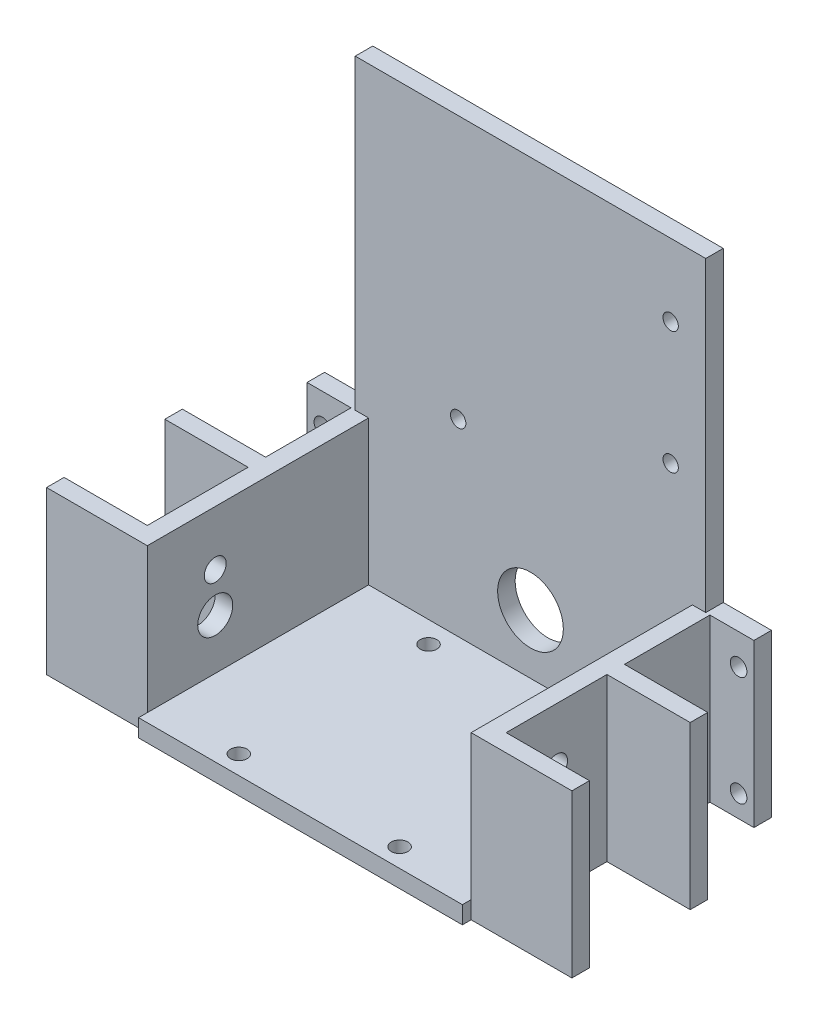
SolidWorks part; units mm, degrees
ref_plane "Front Plane" through (0, 0, 0) normal (0, 0, 1) x (1, 0, 0)
ref_plane "Top Plane" through (0, 0, 0) normal (0, 1, 0) x (1, 0, 0)
ref_plane "Right Plane" through (0, 0, 0) normal (1, 0, 0) x (0, 0, -1)
sketch "Sketch1" plane through (0, 0, 0) normal (0, 1, 0) x (1, 0, 0)
  line L0 (40.9555, 11.5) -> (59.9555, 11.5)
  line L1 (-59.9555, -15.5) -> (59.9555, -15.5)
  line L2 (-59.9555, -15.5) -> (-59.9555, -11.5)
  line L3 (-59.9555, 15.5) -> (59.9555, 15.5)
  line L4 (59.9555, -15.5) -> (59.9555, -11.5)
  line L5 (-59.9555, -15.5) -> (59.9555, 15.5) construction
  line L6 (-59.9555, 15.5) -> (59.9555, -15.5) construction
  line L8 (-40.9555, -11.5) -> (-40.9555, 11.5)
  line L10 (40.9555, -11.5) -> (40.9555, 11.5)
  line L11 (-40.9555, -11.5) -> (40.9555, 11.5) construction
  line L12 (-40.9555, 11.5) -> (40.9555, -11.5) construction
  line L14 (59.9555, -11.5) -> (40.9555, -11.5)
  line L15 (-40.9555, -11.5) -> (-59.9555, -11.5)
  line L16 (59.9555, 11.5) -> (59.9555, 15.5)
  line L17 (-59.9555, 11.5) -> (-40.9555, 11.5)
  line L18 (-59.9555, 11.5) -> (-59.9555, 15.5)
  point P0 (0, 0)
  point P6 (0, 0)
  dimension "D1" = 23
  dimension "D2" = 19
  dimension "D3" = 4
extrude "Boss-Extrude1" add sketch "Sketch1" along normal blind 4
sketch "Sketch2" plane through (0, 4, 0) normal (0, 1, 0) x (1, 0, 0)
  line L12 (-36.9555, 15.5) -> (-59.9555, 15.5)
  line L14 (-36.9555, -15.5) -> (-36.9555, 15.5)
  line L16 (36.9555, -15.5) -> (36.9555, 15.5)
  line L17 (-36.9555, -15.5) -> (36.9555, 15.5) construction
  line L18 (-36.9555, 15.5) -> (36.9555, -15.5) construction
  line L19 (36.9555, -15.5) -> (59.9555, -15.5)
  line L24 (59.9555, 11.5) -> (59.9555, 15.5)
  line L25 (59.9555, 15.5) -> (-59.9555, 15.5)
  line L26 (-59.9555, 15.5) -> (-59.9555, 11.5)
  line L27 (-59.9555, 11.5) -> (-40.9555, 11.5)
  line L28 (-40.9555, 11.5) -> (-40.9555, -11.5)
  line L29 (-40.9555, -11.5) -> (-59.9555, -11.5)
  line L30 (-59.9555, -11.5) -> (-59.9555, -15.5)
  line L31 (-59.9555, -15.5) -> (59.9555, -15.5)
  line L32 (59.9555, -15.5) -> (59.9555, -11.5)
  line L33 (59.9555, -11.5) -> (40.9555, -11.5)
  line L34 (40.9555, -11.5) -> (40.9555, 11.5)
  line L35 (40.9555, 11.5) -> (59.9555, 11.5)
  line L36 (59.9555, 11.5) -> (59.9555, 15.5)
  line L37 (59.9555, 15.5) -> (36.9555, 15.5)
  line L38 (-59.9555, 15.5) -> (-59.9555, 11.5)
  line L39 (-59.9555, 11.5) -> (-40.9555, 11.5)
  line L40 (-40.9555, 11.5) -> (-40.9555, -11.5)
  line L41 (-40.9555, -11.5) -> (-59.9555, -11.5)
  line L42 (-59.9555, -11.5) -> (-59.9555, -15.5)
  line L43 (-59.9555, -15.5) -> (-36.9555, -15.5)
  line L44 (59.9555, -15.5) -> (59.9555, -11.5)
  line L45 (59.9555, -11.5) -> (40.9555, -11.5)
  line L46 (40.9555, -11.5) -> (40.9555, 11.5)
  line L47 (40.9555, 11.5) -> (59.9555, 11.5)
  point P2 (0, 0)
  dimension "D2" = 4
  dimension "D1" = 0
extrude "Boss-Extrude2" add sketch "Sketch2" along normal blind 37 from surface at -4 starting at face at (0, 0, 0)
sketch "Sketch3" plane through (-40.9555, 0, 0) normal (-1, 0, 0) x (0, 0, 1)
  line L0 (0, 37) -> (0, 0) construction
  line L1 (11.5, 37) -> (-11.5, 37) construction
  line L2 (-11.5, 0) -> (11.5, 0) construction
  circle A0 centre (0, 15.5) radius 4
  circle A1 centre (0, 24.5) radius 2.5
  dimension "D1" = 8
  dimension "D2" = 5
  dimension "D3" = 15.5
  dimension "D4" = 24.5
extrude "Cut-Extrude1" cut sketch "Sketch3" against normal through all
sketch "Sketch4" plane through (0, 4, 0) normal (0, 1, 0) x (1, 0, 0)
  line L1 (-36.9555, -17.5) -> (36.9555, -17.5)
  line L2 (-36.9555, -17.5) -> (-36.9555, 35)
  line L3 (-36.9555, 35) -> (36.9555, 35)
  line L4 (36.9555, -17.5) -> (36.9555, 35)
  dimension "D1" = 35
  dimension "D2" = 52.5
extrude "Boss-Extrude3" add sketch "Sketch4" against normal up to surface (4 mm away) up to face at (0, 0, 0)
sketch "Sketch5" plane through (0, 4, 0) normal (0, 1, 0) x (1, 0, 0)
  line L0 (-18.35, -15.5) -> (18.35, -15.5) construction
  line L1 (-18.35, -15.5) -> (-18.35, 35.0806) construction
  line L2 (18.35, -15.5) -> (18.35, 35.0806) construction
  line L3 (-18.35, 35.0806) -> (18.35, 35.0806) construction
  line L4 (-36.9555, -15.5) -> (36.9555, -15.5) construction
  line L6 (0, 35.0806) -> (0, -15.5) construction
  circle A0 centre (-18.35, 30.0806) radius 1.9
  circle A1 centre (18.35, 30.0806) radius 1.9
  circle A2 centre (18.35, -13.2194) radius 1.9
  circle A3 centre (-18.35, -13.2194) radius 1.9
  dimension "D1" = 3.8
  dimension "D2" = 43.3
  dimension "D3" = 36.7
  dimension "D4" = 5
extrude "Cut-Extrude2" cut sketch "Sketch5" against normal blind 37
sketch "Sketch6" plane through (0, 4, 0) normal (0, 1, 0) x (1, 0, 0)
  line L0 (-36.9555, 15.5) -> (-36.9555, 35)
  line L1 (-36.9555, 35) -> (36.9555, 35)
  line L2 (36.9555, 35) -> (36.9555, 15.5)
  line L3 (36.9555, 15.5) -> (40.9555, 15.5)
  line L4 (36.9555, 15.5) -> (59.9555, 15.5) construction
  line L5 (40.9555, 15.5) -> (40.9555, 35)
  line L7 (-40.9555, 35) -> (-40.9555, 15.5)
  line L8 (-59.9555, 15.5) -> (-36.9555, 15.5) construction
  line L9 (-40.9555, 15.5) -> (-36.9555, 15.5)
  line L10 (40.9555, 35) -> (51, 35)
  line L11 (51, 35) -> (51, 39)
  line L12 (51, 39) -> (-51, 39)
  line L13 (-51, 39) -> (-51, 35)
  line L14 (-51, 35) -> (-40.9555, 35)
  point P12 (0, 39)
  point P21 (0, 35)
  dimension "D1" = 4
  dimension "D2" = 102
extrude "Boss-Extrude4" add sketch "Sketch6" along normal blind 37 from surface at -4 starting at face at (-18.35, 0, 11.3194)
sketch "Sketch7" plane through (0, 0, -39) normal (0, 0, -1) x (-1, 0, 0)
  line L0 (-47.5, 5) -> (-47.5, 30) construction
  line L1 (-47.5, 5) -> (47.5, 5) construction
  line L2 (-47.5, 30) -> (47.5, 30) construction
  line L3 (47.5, 5) -> (47.5, 30) construction
  line L4 (-47.5, 5) -> (47.5, 30) construction
  line L5 (-47.5, 30) -> (47.5, 5) construction
  line L6 (40.9555, 37) -> (-40.9555, 37) construction
  line L7 (40.9555, 0) -> (-40.9555, 0) construction
  circle A0 centre (-47.5, 30) radius 1.9
  circle A1 centre (47.5, 30) radius 1.9
  circle A2 centre (47.5, 5) radius 1.9
  circle A3 centre (-47.5, 5) radius 1.9
  circle A4 centre (0, 17.5) radius 7.5
  point P1 (0, 17.5)
  point P12 (0, 37)
  dimension "D1" = 3.8
  dimension "D5" = 15
  dimension "D2" = 95
  dimension "D3" = 25
  dimension "D4" = 5
extrude "Cut-Extrude4" cut sketch "Sketch7" against normal up to surface (4 mm away) up to face at (0, 20.5, -35)
sketch "Sketch8" plane through (0, 0, -39) normal (0, 0, -1) x (-1, 0, 0)
  line L0 (-32, 62.5) -> (-32, 90.5) construction
  line L1 (-32, 62.5) -> (-32, 47) construction
  line L2 (-32, 47) -> (16.5, 47) construction
  line L3 (-40, 107) -> (-40, 37)
  line L4 (-40, 107) -> (40, 107)
  line L5 (-40, 37) -> (40, 37)
  line L6 (40, 107) -> (40, 37)
  line L7 (-40, 107) -> (40, 37) construction
  line L8 (-40, 37) -> (40, 107) construction
  line L10 (51, 37) -> (-51, 37) construction
  circle A0 centre (0, 17.5) radius 7.5 construction
  circle A1 centre (-32, 90.5) radius 1.75
  circle A2 centre (-32, 62.5) radius 1.75
  circle A3 centre (16.5, 47) radius 1.75
  point P9 (0, 0)
  point P10 (0, 72)
  point P18 (0, 0)
  point P19 (0, 0)
  point P20 (0, 0)
  dimension "D2" = 3.5
  dimension "D1" = 32
  dimension "D3" = 28
  dimension "D4" = 15.5
  dimension "D5" = 48.5
  dimension "D6" = 80
  dimension "D7" = 10
  dimension "D8" = 60
extrude "Boss-Extrude5" add sketch "Sketch8" against normal up to surface (4 mm away) up to face at (7.5, 17.5, -35)
